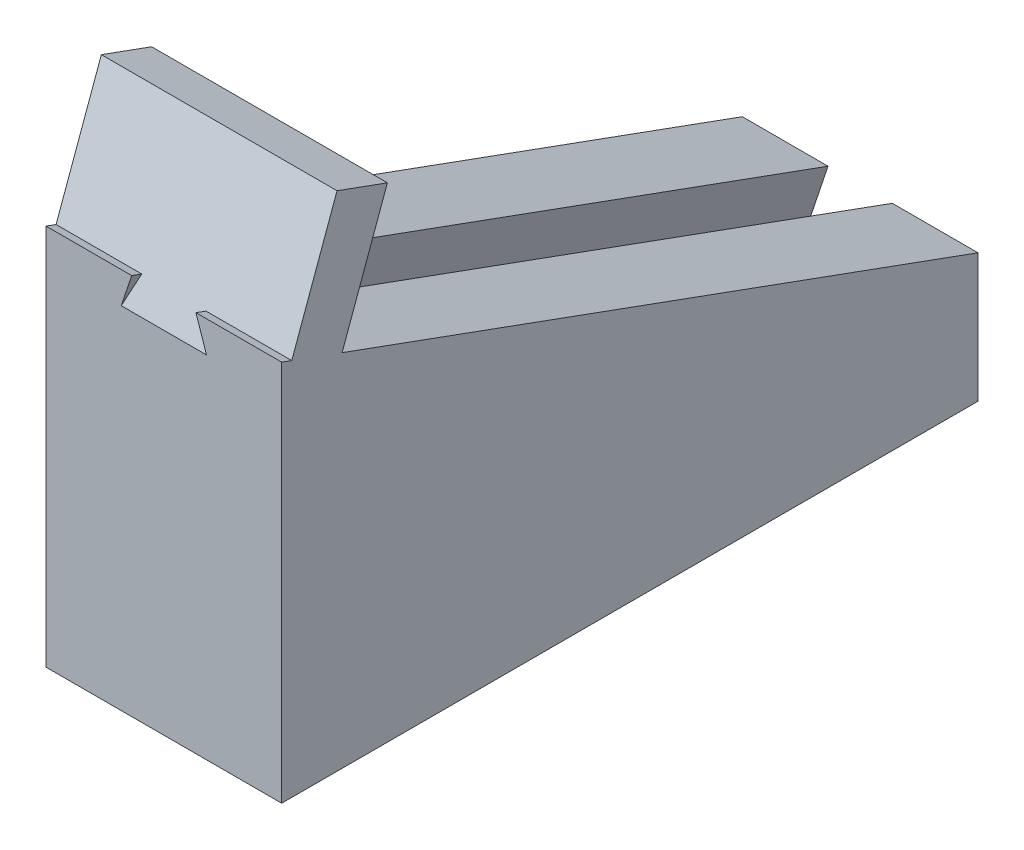
SolidWorks part; units mm, degrees
ref_plane "Front Plane" through (0, 0, 0) normal (0, 0, 1) x (1, 0, 0)
ref_plane "Top Plane" through (0, 0, 0) normal (0, 1, 0) x (1, 0, 0)
ref_plane "Right Plane" through (0, 0, 0) normal (1, 0, 0) x (0, 0, -1)
sketch "Sketch2" plane through (0, 0, 0) normal (1, 0, 0) x (0, 0, -1)
  line L0 (-7.4285, -9.7829) -> (25.0715, -9.7829)
  line L1 (25.0715, -9.7829) -> (25.0715, -3.7829)
  line L2 (25.0715, -3.7829) -> (-7.4285, 8.0461)
  line L3 (-7.4285, 8.0461) -> (-7.4285, -9.7829)
  dimension "D1" = 32.5
  dimension "D2" = 6
  dimension "D3" = 20
extrude "Boss-Extrude1" add sketch "Sketch2" against normal blind 11
sketch "Sketch3" plane through (0, 0, -25.0715) normal (0, 0, -1) x (-1, 0, 0)
  line L0 (3, -6.7829) -> (8, -6.7829)
  line L2 (8, -6.7829) -> (7, -3.7829)
  line L3 (11, -3.7829) -> (0, -3.7829) construction
  line L4 (7, -3.7829) -> (4, -3.7829)
  line L5 (4, -3.7829) -> (3, -6.7829)
  line L6 (0, -9.7829) -> (0, -3.7829) construction
  line L7 (11, -9.7829) -> (0, -9.7829) construction
  dimension "D1" = 3
  dimension "D2" = 5
  dimension "D3" = 3
  dimension "D4" = 3
sketch "Sketch5" plane through (-11, 0, 0) normal (-1, 0, 0) x (0, 0, 1)
  line L0 (-25.0715, -6.9755) -> (8.7574, 5.3372)
  line L1 (-25.0715, -9.7829) -> (-25.0715, -3.7829) construction
  line L3 (-25.0715, -3.7829) -> (7.4285, 8.0461) construction
  dimension "D1" = 3
  dimension "D2" = 36
sweep "Cut-Sweep3" cut profiles "Sketch3" path "Sketch5"
sketch "Sketch6" plane through (-11, 0, 0) normal (-1, 0, 0) x (0, 0, 1)
  line L0 (5.5736, 4.371) -> (7.4285, 5.0461)
  line L1 (5.5736, 4.371) -> (2.4954, 12.8282)
  line L2 (4.8446, 13.6832) -> (7.4285, 6.5842)
  line L3 (2.4954, 12.8282) -> (4.8446, 13.6832)
  line L5 (7.4285, 8.0461) -> (7.4285, -9.7829) construction
  line L6 (7.4285, 6.5842) -> (7.4285, 5.0461)
  line L8 (-25.0715, -3.7829) -> (7.4285, 8.0461) construction
  dimension "D1" = 9
  dimension "D2" = 2.5
  dimension "D3" = 0.5
extrude "Boss-Extrude2" add sketch "Sketch6" against normal up to surface (11 mm away) up to face at (0, -3.8257, -8.8215)
